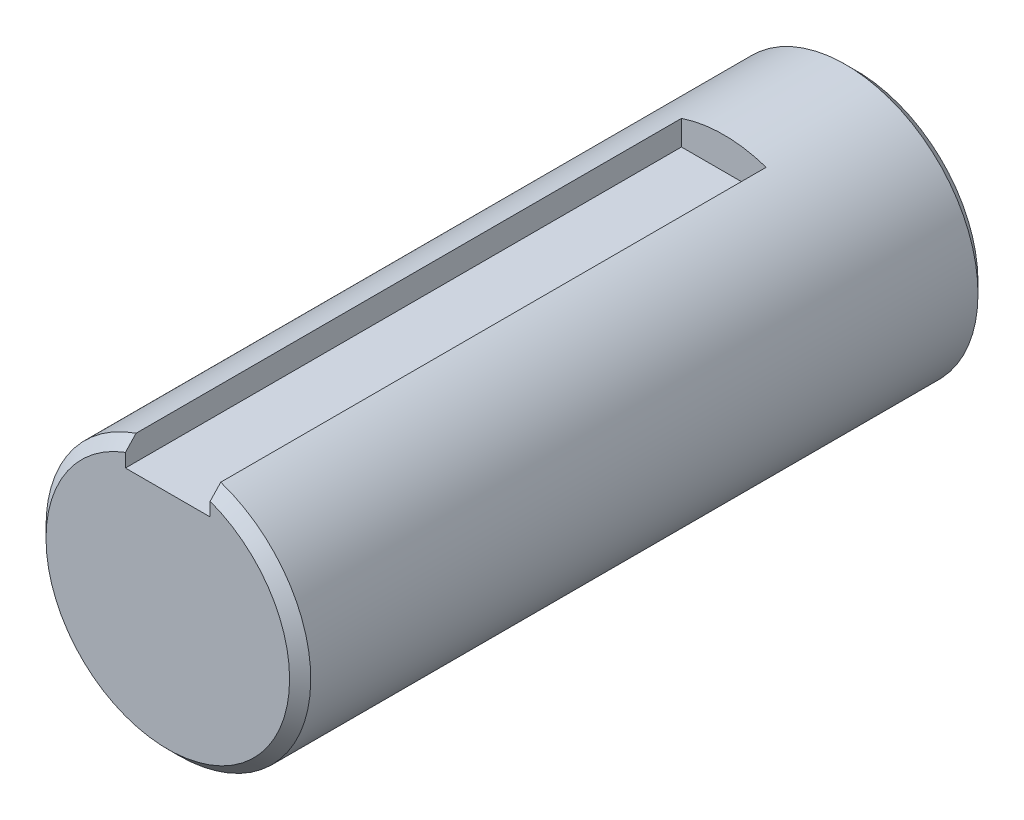
SolidWorks part; units mm, degrees
material "Gray Cast Iron"
ref_plane "Front Plane" through (0, 0, 0) normal (0, 0, 1) x (1, 0, 0)
ref_plane "Top Plane" through (0, 0, 0) normal (0, 1, 0) x (1, 0, 0)
ref_plane "Right Plane" through (0, 0, 0) normal (1, 0, 0) x (0, 0, -1)
sketch "Sketch1" plane through (0, 0, 0) normal (0, 0, 1) x (1, 0, 0)
  line L0 (0, -2.8024) -> (0, -50002.8024) construction
  line L1 (-8, 19) -> (8, 19)
  line L3 (-8, 19) -> (-8, 23.6854)
  line L4 (8, 19) -> (8, 23.6854)
  arc A0 (-8, 23.6854) -> (8, 23.6854) centre (0, 0) ccw
  point P1 (-8, 19)
  point P6 (0, -25)
  point P9 (0, 19)
  point P10 (8, 19)
  point P12 (8, 19)
  point P13 (-8, 23.6854)
  point P14 (-8, 20.7051)
  point P15 (0, 0)
  dimension "D1" = 50
  dimension "D2" = 16
  dimension "D3" = 44
extrude "Boss-Extrude1" add sketch "Sketch1" along normal blind 130
sketch "Sketch2" plane through (0, 0, 0) normal (0, 0, -1) x (-1, 0, 0)
  line L0 (-8, 23.6854) -> (-8, 19)
  line L1 (-8, 19) -> (8, 19)
  line L2 (8, 19) -> (8, 23.6854)
  arc A0 (8, 23.6854) -> (-8, 23.6854) centre (0, 0) ccw
  arc A1 (-8, 23.6854) -> (8, 23.6854) centre (0, 0) ccw construction
extrude "Boss-Extrude2" add sketch "Sketch2" against normal blind 25
chamfer "Chamfer1" distance 2 angle 45 2 edges at (25, 0, 0) (0, -25, 130)
